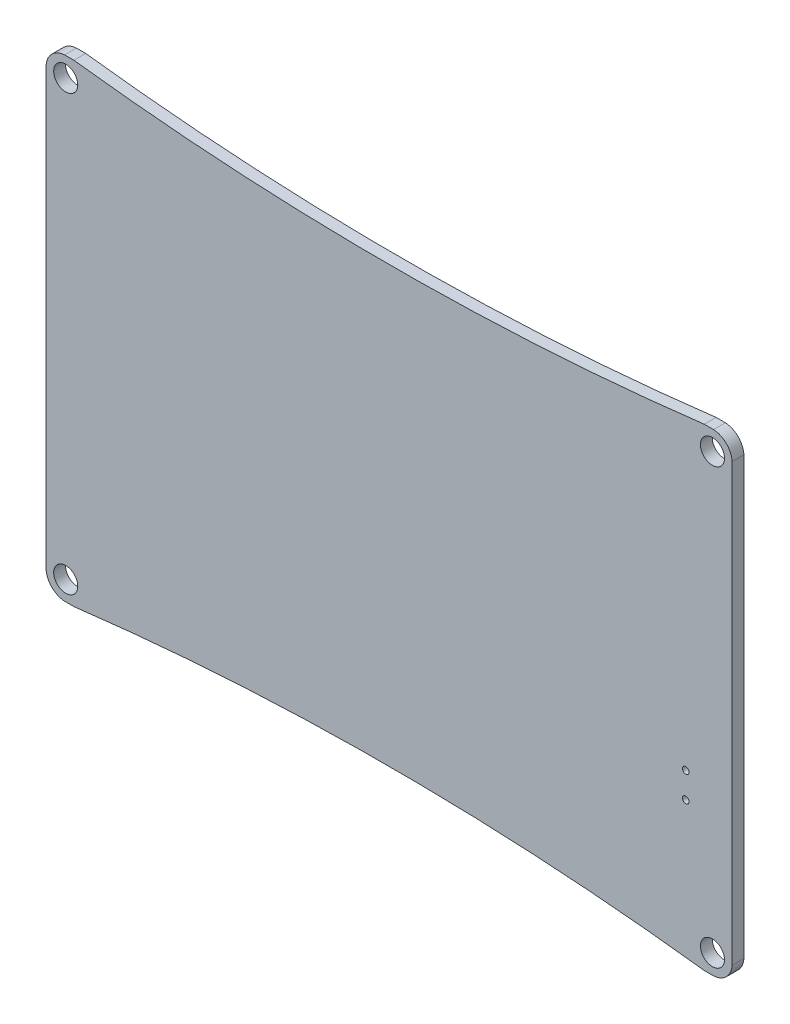
SolidWorks part; units mm, degrees
ref_plane "Front Plane" through (0, 0, 0) normal (0, 0, 1) x (1, 0, 0)
ref_plane "Top Plane" through (0, 0, 0) normal (0, 1, 0) x (1, 0, 0)
ref_plane "Right Plane" through (0, 0, 0) normal (1, 0, 0) x (0, 0, -1)
sketch "Sketch1" plane through (0, 0, 0) normal (0, 0, 1) x (1, 0, 0)
  line L0 (2.54, 62.89) -> (2.54, 3.15)
  line L1 (5.08, 0.61) -> (6.35, 0.61)
  line L2 (92.71, 0.61) -> (93.98, 0.61)
  line L3 (96.52, 3.15) -> (96.52, 62.89)
  line L4 (93.98, 65.43) -> (92.71, 65.43)
  line L5 (6.35, 65.43) -> (5.08, 65.43)
  arc A0 (2.54, 3.15) -> (5.08, 0.61) centre (5.2205, 3.2905) ccw
  arc A1 (6.35, 0.61) -> (92.71, 0.61) centre (49.53, -351.0629) cw
  arc A2 (93.98, 0.61) -> (96.52, 3.15) centre (93.8395, 3.2905) ccw
  arc A3 (96.52, 62.89) -> (93.98, 65.43) centre (93.8395, 62.7495) ccw
  arc A4 (92.71, 65.43) -> (6.35, 65.43) centre (49.53, 417.1029) cw
  arc A5 (5.08, 65.43) -> (2.54, 62.89) centre (5.2205, 62.7495) ccw
  dimension "D1" = 59.459
  dimension "D2" = 64.82
  dimension "D3" = 93.98
  dimension "D4" = 88.619
extrude "Board_Outline" add sketch "Sketch1" along normal blind 1.62 separate body
sketch "Sketch2" plane through (0, 0, 0) normal (0, 0, 1) x (1, 0, 0)
  circle A0 centre (90.17, 23.09) radius 0.45
  circle A1 centre (90.17, 19.59) radius 0.45
extrude "NPTH" cut sketch "Sketch2" along normal through all
sketch "Sketch3" plane through (0, 0, 0) normal (0, 0, 1) x (1, 0, 0)
  circle A0 centre (93.83, 3.28) radius 1.65
  circle A1 centre (5.23, 3.28) radius 1.65
  circle A2 centre (5.23, 62.76) radius 1.65
  circle A3 centre (93.83, 62.76) radius 1.65
extrude "PTH" cut sketch "Sketch3" along normal through all
